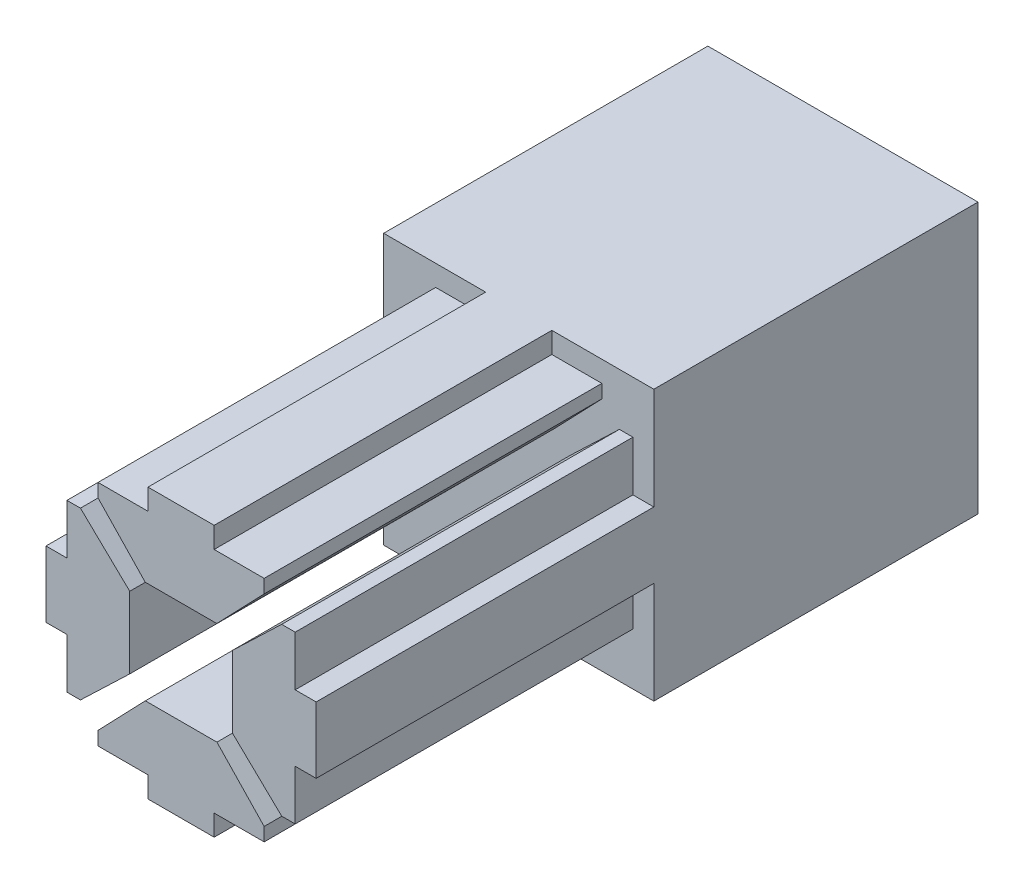
SolidWorks part; units mm, degrees
ref_plane "Plan de face" through (0, 0, 0) normal (0, 0, 1) x (1, 0, 0)
ref_plane "Plan de dessus" through (0, 0, 0) normal (0, 1, 0) x (1, 0, 0)
ref_plane "Plan de droite" through (0, 0, 0) normal (1, 0, 0) x (0, 0, -1)
sketch "Esquisse1" plane through (0, 0, 0) normal (0, 0, 1) x (1, 0, 0)
  line L1 (-10, -10) -> (10, -10)
  line L2 (-10, -10) -> (-10, 10)
  line L3 (-10, 10) -> (10, 10)
  line L4 (10, -10) -> (10, 10)
  line L5 (-10, -10) -> (10, 10) construction
  line L6 (-10, 10) -> (10, -10) construction
  point P0 (0, 0)
extrude "Boss.-Extru.1" add sketch "Esquisse1" along normal blind 24
sketch "Esquisse2" plane through (0, 0, 24) normal (0, 0, 1) x (1, 0, 0)
  line L0 (-2.45, -10) -> (-2.45, -8.45)
  line L1 (-10, -10) -> (10, -10) construction
  line L2 (-2.45, -8.45) -> (-6.15, -8.45)
  line L3 (-6.15, -8.45) -> (-6.15, -7.45)
  line L4 (-6.15, -7.45) -> (-2.6456, -3.8)
  line L5 (-2.6456, -3.8) -> (2.6544, -3.8)
  line L6 (2.6544, -3.8) -> (6.15, -7.4585)
  line L7 (6.15, -7.4585) -> (6.15, -8.45)
  line L8 (6.15, -8.45) -> (2.45, -8.45)
  line L9 (2.45, -8.45) -> (2.45, -10)
  line L10 (-10, 10) -> (-10, -10) construction
  line L11 (10, -10) -> (10, 10) construction
  line L16 (10, -10) -> (10, 10)
  line L17 (10, 10) -> (-10, 10)
  line L18 (-10, 10) -> (-10, -10)
  line L19 (-10, -10) -> (10, -10)
  line L23 (-2.45, -10) -> (2.45, -10)
  dimension "D1" = 1.55
  dimension "D2" = 3.7
  dimension "D3" = 1
  dimension "D4" = 5.06
  dimension "D5" = 5.3
  dimension "D6" = 7.55
  dimension "D7" = 5.06
  dimension "D8" = 6.2
  dimension "D9" = 7.55
  dimension "D10" = 1.55
  dimension "D11" = 3.7
  dimension "D12" = 0.9915
  dimension "D13" = 0
extrude "Boss.-Extru.2" add sketch "Esquisse2" along normal blind 25
sketch "Esquisse3" plane through (0, 0, 24) normal (0, 0, 1) x (1, 0, 0)
  line L0 (10, -2.45) -> (8.45, -2.45)
  line L1 (10, -10) -> (10, 10) construction
  line L2 (8.45, -2.45) -> (8.45, -6.15)
  line L3 (8.45, -6.15) -> (7.45, -6.15)
  line L4 (7.45, -6.15) -> (3.8, -2.6456)
  line L5 (3.8, -2.6456) -> (3.8, 2.6544)
  line L6 (8.45, 6.15) -> (7.45, 6.15)
  line L7 (7.45, 6.15) -> (3.8, 2.6544)
  line L8 (8.45, 6.15) -> (8.45, 2.45)
  line L9 (8.45, 2.45) -> (10, 2.45)
  line L10 (2.45, -10) -> (10, -10) construction
  line L25 (-2.45, -10) -> (-2.45, -8.45)
  line L26 (-2.45, -8.45) -> (-6.15, -8.45)
  line L27 (-6.15, -8.45) -> (-6.15, -7.45)
  line L28 (-6.15, -7.45) -> (-2.6456, -3.8)
  line L29 (-2.6456, -3.8) -> (2.6544, -3.8)
  line L30 (2.6544, -3.8) -> (6.15, -7.4585)
  line L31 (6.15, -7.4585) -> (6.15, -8.45)
  line L32 (6.15, -8.45) -> (2.45, -8.45)
  line L33 (2.45, -8.45) -> (2.45, -10)
  line L34 (2.45, -10) -> (10, -10)
  line L35 (10, -10) -> (10, 10)
  line L36 (10, 10) -> (-10, 10)
  line L37 (-10, 10) -> (-10, -10)
  line L38 (-10, -10) -> (-2.45, -10)
  line L49 (10, -2.45) -> (10, 2.45)
  dimension "D1" = 7.55
  dimension "D2" = 1.55
  dimension "D3" = 3.7
  dimension "D4" = 1
  dimension "D5" = 5.06
  dimension "D6" = 0
  dimension "D7" = 6.2
  dimension "D8" = 7.55
  dimension "D9" = 1.55
  dimension "D10" = 3.7
extrude "Boss.-Extru.3" add sketch "Esquisse3" along normal blind 25
sketch "Esquisse4" plane through (0, 0, 24) normal (0, 0, 1) x (1, 0, 0)
  line L0 (2.45, 10) -> (2.45, 8.45)
  line L1 (10, 10) -> (-10, 10) construction
  line L2 (2.45, 8.45) -> (6.15, 8.45)
  line L3 (6.15, 8.45) -> (6.15, 7.45)
  line L4 (6.15, 7.45) -> (2.6456, 3.8)
  line L5 (2.6456, 3.8) -> (-2.6544, 3.8)
  line L6 (-2.6544, 3.8) -> (-6.15, 7.4585)
  line L7 (-6.15, 7.4585) -> (-6.15, 8.45)
  line L8 (-6.15, 8.45) -> (-2.45, 8.45)
  line L9 (-2.45, 8.45) -> (-2.45, 10)
  line L34 (8.45, 2.45) -> (10, 2.45)
  line L35 (10, 2.45) -> (10, 10)
  line L36 (10, 10) -> (-10, 10)
  line L37 (-10, 10) -> (-10, -10)
  line L38 (-10, -10) -> (-2.45, -10)
  line L39 (-2.45, -10) -> (-2.45, -8.45)
  line L40 (-2.45, -8.45) -> (-6.15, -8.45)
  line L41 (-6.15, -8.45) -> (-6.15, -7.45)
  line L42 (-6.15, -7.45) -> (-2.6456, -3.8)
  line L43 (-2.6456, -3.8) -> (2.6544, -3.8)
  line L44 (2.6544, -3.8) -> (6.15, -7.4585)
  line L45 (6.15, -7.4585) -> (6.15, -8.45)
  line L46 (6.15, -8.45) -> (2.45, -8.45)
  line L47 (2.45, -8.45) -> (2.45, -10)
  line L48 (2.45, -10) -> (10, -10)
  line L49 (10, -10) -> (10, -2.45)
  line L50 (10, -2.45) -> (8.45, -2.45)
  line L51 (8.45, -2.45) -> (8.45, -6.15)
  line L52 (8.45, -6.15) -> (7.45, -6.15)
  line L53 (7.45, -6.15) -> (3.8, -2.6456)
  line L54 (3.8, -2.6456) -> (3.8, 2.6544)
  line L55 (3.8, 2.6544) -> (7.45, 6.15)
  line L56 (7.45, 6.15) -> (8.45, 6.15)
  line L57 (8.45, 6.15) -> (8.45, 2.45)
  line L60 (2.45, 10) -> (-2.45, 10)
  dimension "D1" = 7.55
  dimension "D2" = 1.55
  dimension "D3" = 3.7
  dimension "D4" = 1
  dimension "D5" = 6.2
  dimension "D6" = 5.06
  dimension "D7" = 7.55
  dimension "D8" = 1.55
  dimension "D9" = 3.7
  dimension "D10" = 5.3
  dimension "D11" = 5.06
  dimension "D12" = 0.9915
  dimension "D13" = 0
extrude "Boss.-Extru.4" add sketch "Esquisse4" along normal blind 25
sketch "Esquisse5" plane through (0, 0, 24) normal (0, 0, 1) x (1, 0, 0)
  line L0 (-10, 2.45) -> (-8.45, 2.45)
  line L1 (-10, 10) -> (-10, -10) construction
  line L2 (-8.45, 2.45) -> (-8.45, 6.15)
  line L3 (-8.45, 6.15) -> (-7.45, 6.15)
  line L4 (-7.45, 6.15) -> (-3.8, 2.6456)
  line L5 (-3.8, 2.6456) -> (-3.8, -2.6544)
  line L6 (-3.8, -2.6544) -> (-7.45, -6.15)
  line L7 (-7.45, -6.15) -> (-8.45, -6.15)
  line L8 (-8.45, -6.15) -> (-8.45, -2.45)
  line L9 (-8.45, -2.45) -> (-10, -2.45)
  line L10 (-2.45, 10) -> (-10, 10) construction
  line L11 (-10, -10) -> (-2.45, -10) construction
  line L46 (-2.45, 8.45) -> (-2.45, 10)
  line L47 (-2.45, 10) -> (-10, 10)
  line L48 (-10, 10) -> (-10, -10)
  line L49 (-10, -10) -> (-2.45, -10)
  line L50 (-2.45, -10) -> (-2.45, -8.45)
  line L51 (-2.45, -8.45) -> (-6.15, -8.45)
  line L52 (-6.15, -8.45) -> (-6.15, -7.45)
  line L53 (-6.15, -7.45) -> (-2.6456, -3.8)
  line L54 (-2.6456, -3.8) -> (2.6544, -3.8)
  line L55 (2.6544, -3.8) -> (6.15, -7.4585)
  line L56 (6.15, -7.4585) -> (6.15, -8.45)
  line L57 (6.15, -8.45) -> (2.45, -8.45)
  line L58 (2.45, -8.45) -> (2.45, -10)
  line L59 (2.45, -10) -> (10, -10)
  line L60 (10, -10) -> (10, -2.45)
  line L61 (10, -2.45) -> (8.45, -2.45)
  line L62 (8.45, -2.45) -> (8.45, -6.15)
  line L63 (8.45, -6.15) -> (7.45, -6.15)
  line L64 (7.45, -6.15) -> (3.8, -2.6456)
  line L65 (3.8, -2.6456) -> (3.8, 2.6544)
  line L66 (3.8, 2.6544) -> (7.45, 6.15)
  line L67 (7.45, 6.15) -> (8.45, 6.15)
  line L68 (8.45, 6.15) -> (8.45, 2.45)
  line L69 (8.45, 2.45) -> (10, 2.45)
  line L70 (10, 2.45) -> (10, 10)
  line L71 (10, 10) -> (2.45, 10)
  line L72 (2.45, 10) -> (2.45, 8.45)
  line L73 (2.45, 8.45) -> (6.15, 8.45)
  line L74 (6.15, 8.45) -> (6.15, 7.45)
  line L75 (6.15, 7.45) -> (2.6456, 3.8)
  line L76 (2.6456, 3.8) -> (-2.6544, 3.8)
  line L77 (-2.6544, 3.8) -> (-6.15, 7.4585)
  line L78 (-6.15, 7.4585) -> (-6.15, 8.45)
  line L79 (-6.15, 8.45) -> (-2.45, 8.45)
  line L82 (-10, 2.45) -> (-10, -2.45)
  dimension "D1" = 7.55
  dimension "D2" = 1.55
  dimension "D3" = 3.7
  dimension "D4" = 1
  dimension "D5" = 5.06
  dimension "D6" = 6.2
  dimension "D7" = 7.55
  dimension "D8" = 1.55
  dimension "D9" = 3.7
  dimension "D10" = 5.3
  dimension "D11" = 1
  dimension "D12" = 5.0539
  dimension "D13" = 0
extrude "Boss.-Extru.5" add sketch "Esquisse5" along normal blind 25
sketch "Esquisse6" plane through (0, 0, 0) normal (0, 0, -1) x (-1, 0, 0)
  circle A0 centre (0, 0) radius 3
extrude "Enlèv. mat.-Extru.1" cut sketch "Esquisse6" against normal blind 22
